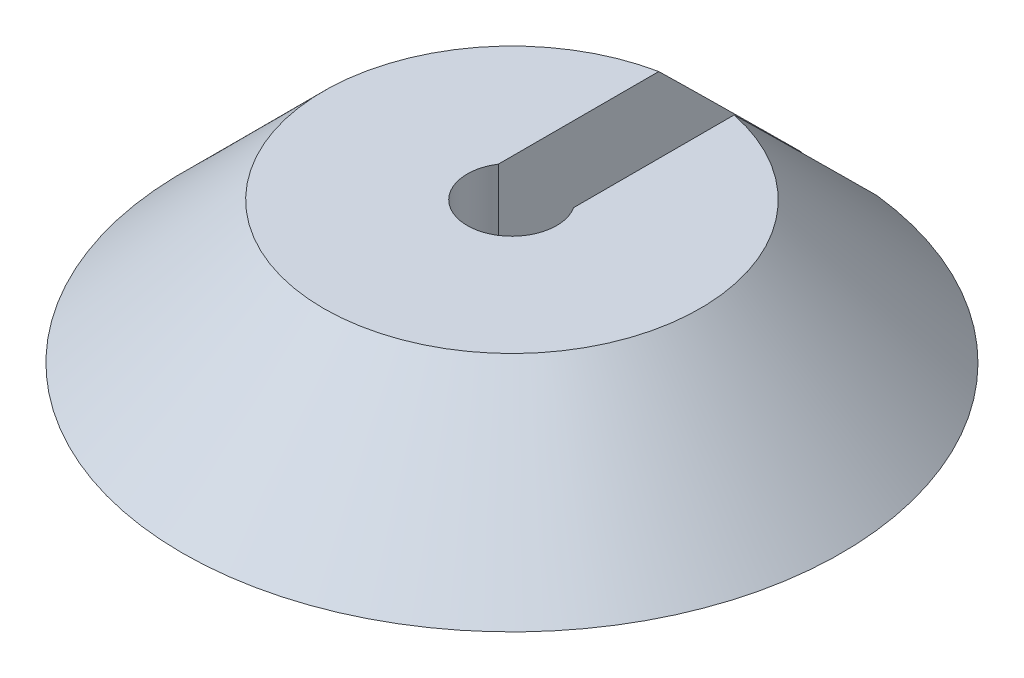
SolidWorks part; units mm, degrees
ref_plane "Front Plane" through (0, 0, 0) normal (0, 0, 1) x (1, 0, 0)
ref_plane "Top Plane" through (0, 0, 0) normal (0, 1, 0) x (1, 0, 0)
ref_plane "Right Plane" through (0, 0, 0) normal (1, 0, 0) x (0, 0, -1)
sketch "Sketch1" plane through (0, 0, 0) normal (0, 0, 1) x (1, 0, 0)
  line L0 (0, -1026.3556) -> (0, 50291.4229) construction
  line L1 (0, 0) -> (7, 0)
  line L2 (7, 0) -> (4, 3)
  line L3 (4, 3) -> (0, 3)
  line L4 (0, 3) -> (0, 0)
  dimension "D1" = 4
  dimension "D2" = 7
  dimension "D3" = 3
revolve "Revolve1" add sketch "Sketch1" angle 360 about L0
sketch "Sketch2" plane through (0, 3, 0) normal (0, 1, 0) x (1, 0, 0)
  circle A0 centre (0, 0) radius 0.95
  dimension "D1" = 1.9
extrude "Cut-Extrude1" cut sketch "Sketch2" against normal through all both and the other way through all
sketch "Sketch3" plane through (0, 3, 0) normal (0, 1, 0) x (1, 0, 0)
  line L0 (-0.8, 0.5123) -> (-0.8, 6.9541)
  line L1 (0.8, 0.5123) -> (0.8, 6.9541)
  circle A0 centre (0, 0) radius 0.95 construction
  circle A1 centre (0, 0) radius 7 construction
  arc A4 (0.8, 6.9541) -> (-0.8, 6.9541) centre (0, 0) ccw
  arc A7 (0.8, 0.5123) -> (-0.8, 0.5123) centre (0, 0) ccw
  point P12 (-0.7, -0.6423)
  point P14 (0, 0)
  point P15 (0, 0)
  point P16 (1.3816, 6.8623)
  point P17 (-1.4332, 6.8517)
  dimension "D1" = 1.6
extrude "Cut-Extrude2" cut sketch "Sketch3" against normal through all both and the other way through all
